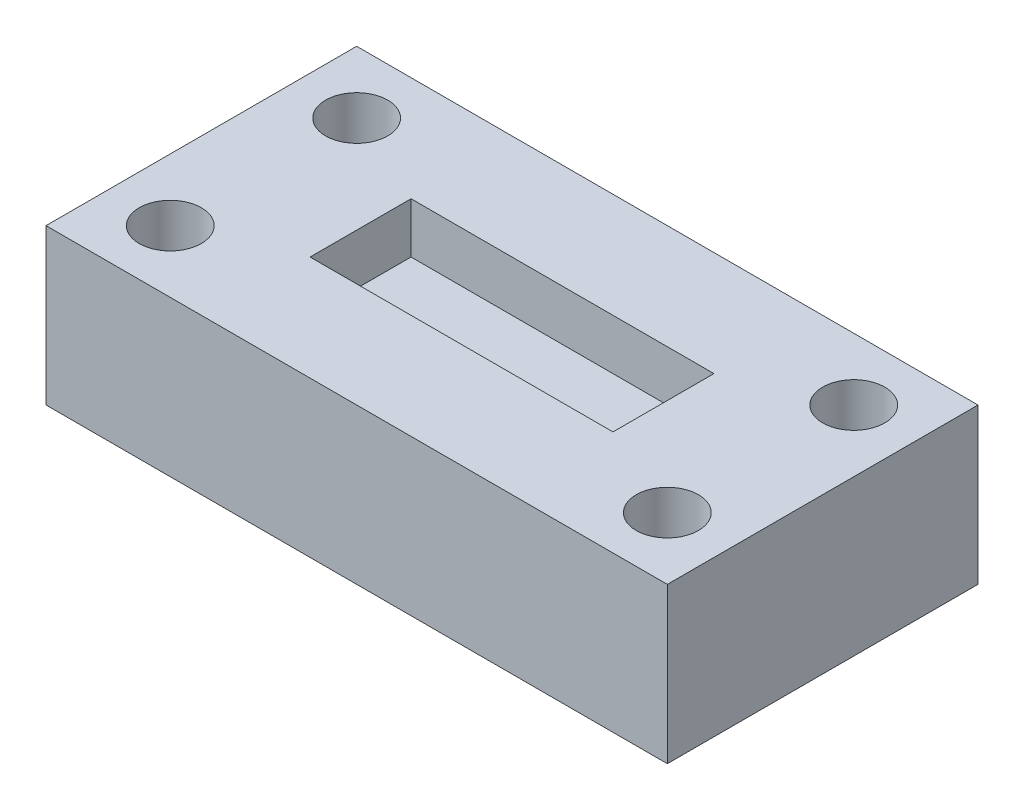
SolidWorks part; units mm, degrees
ref_plane "Front Plane" through (0, 0, 0) normal (0, 0, 1) x (1, 0, 0)
ref_plane "Top Plane" through (0, 0, 0) normal (0, 1, 0) x (1, 0, 0)
ref_plane "Right Plane" through (0, 0, 0) normal (1, 0, 0) x (0, 0, -1)
sketch "Sketch1" plane through (0, 0, 0) normal (0, 1, 0) x (1, 0, 0)
  line L0 (-16, -6) -> (-16, 6) construction
  line L1 (-20, -10) -> (20, -10)
  line L2 (-20, -10) -> (-20, 10)
  line L3 (-20, 10) -> (20, 10)
  line L4 (20, -10) -> (20, 10)
  line L5 (-20, -10) -> (20, 10) construction
  line L6 (-20, 10) -> (20, -10) construction
  line L7 (-16, 6) -> (16, 6) construction
  line L8 (16, -6) -> (16, 6) construction
  line L9 (-16, -6) -> (16, -6) construction
  circle A0 centre (-16, 6) radius 2
  circle A1 centre (16, 6) radius 2
  circle A2 centre (16, -6) radius 2
  circle A3 centre (-16, -6) radius 2
  point P0 (0, 0)
  dimension "D4" = 4
  dimension "D1" = 20
  dimension "D2" = 40
  dimension "D3" = 4
extrude "Boss-Extrude1" add sketch "Sketch1" along normal mid plane 10
sketch "Sketch2" plane through (0, 5, 0) normal (0, 1, 0) x (1, 0, 0)
  line L1 (-9.75, -3.25) -> (9.75, -3.25)
  line L2 (-9.75, -3.25) -> (-9.75, 3.25)
  line L3 (-9.75, 3.25) -> (9.75, 3.25)
  line L4 (9.75, -3.25) -> (9.75, 3.25)
  line L5 (-9.75, -3.25) -> (9.75, 3.25) construction
  line L6 (-9.75, 3.25) -> (9.75, -3.25) construction
  point P0 (0, 0)
  dimension "D1" = 6.5
  dimension "D2" = 19.5
extrude "Cut-Extrude1" cut sketch "Sketch2" against normal mid plane 6.5
mirror "Mirror1" about plane through (0, 0, 0) normal (0, 1, 0) of "Cut-Extrude1"
